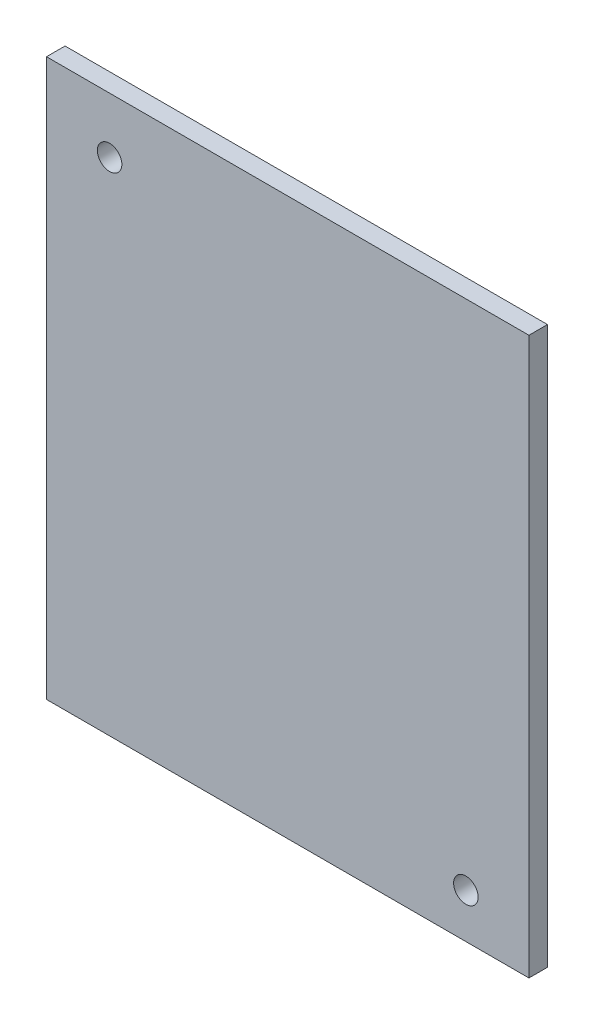
SolidWorks part; units mm, degrees
ref_plane "Front Plane" through (0, 0, 0) normal (0, 0, 1) x (1, 0, 0)
ref_plane "Top Plane" through (0, 0, 0) normal (0, 1, 0) x (1, 0, 0)
ref_plane "Right Plane" through (0, 0, 0) normal (1, 0, 0) x (0, 0, -1)
sketch "Sketch1" plane through (0, 0, 0) normal (0, 0, 1) x (1, 0, 0)
  line L1 (-32.5, 155.4787) -> (32.5, 155.4787)
  line L2 (-32.5, 155.4787) -> (-32.5, 80.4787)
  line L3 (-32.5, 80.4787) -> (32.5, 80.4787)
  line L4 (32.5, 155.4787) -> (32.5, 80.4787)
  line L5 (-32.5, 155.4787) -> (32.5, 80.4787) construction
  line L6 (-32.5, 80.4787) -> (32.5, 155.4787) construction
  line L8 (0, 156) -> (0, 79.9573) construction
  line L11 (43, 156) -> (-43, 156) construction
  line L12 (-25, 79.9573) -> (25, 79.9573) construction
  circle A1 centre (-24, 147.9787) radius 1.65
  circle A2 centre (24, 86.4787) radius 1.65
  point P0 (0, 117.9787)
  point P14 (0, 117.9787)
  dimension "D3" = 7.5
  dimension "D5" = 3.3
  dimension "D4" = 8.5
  dimension "D6" = 3.3
  dimension "D1" = 65
  dimension "D2" = 75
  dimension "D7" = 6
  dimension "D8" = 8.5
extrude "Boss-Extrude1" add sketch "Sketch1" along normal blind 2.5
